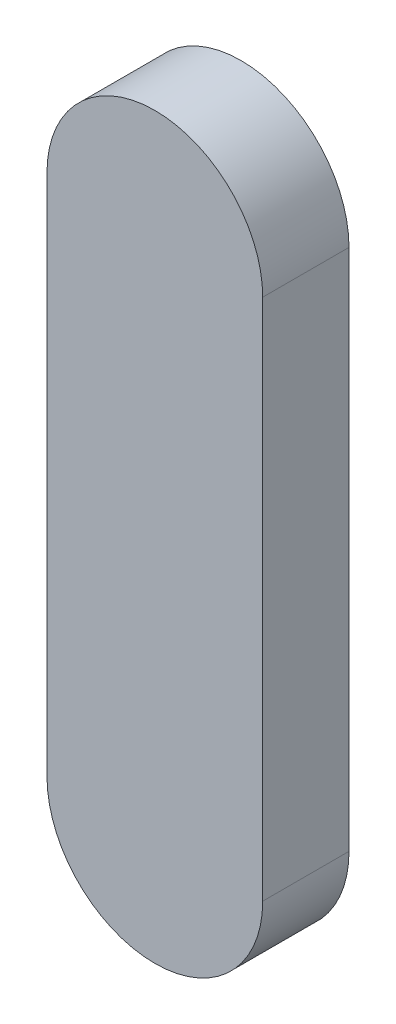
SolidWorks part; units mm, degrees
ref_plane "Front Plane" through (0, 0, 0) normal (0, 0, 1) x (1, 0, 0)
ref_plane "Top Plane" through (0, 0, 0) normal (0, 1, 0) x (1, 0, 0)
ref_plane "Right Plane" through (0, 0, 0) normal (1, 0, 0) x (0, 0, -1)
sketch "Sketch1" plane through (0, 0, 0) normal (0, 0, 1) x (1, 0, 0)
  line L2 (104.7056, -39.4482) -> (104.7056, -24.0518)
  line L3 (98.3556, -24.0518) -> (98.3556, -39.4482)
  line L4 (104.7056, -39.4482) -> (104.7056, -24.0518)
  line L5 (98.3556, -24.0518) -> (98.3556, -39.4482)
  arc A2 (98.3556, -39.4482) -> (104.7056, -39.4482) centre (101.5306, -39.4482) ccw
  arc A3 (104.7056, -24.0518) -> (98.3556, -24.0518) centre (101.5306, -24.0518) ccw
  arc A4 (98.3556, -39.4482) -> (104.7056, -39.4482) centre (101.5306, -39.4482) ccw
  arc A5 (104.7056, -24.0518) -> (98.3556, -24.0518) centre (101.5306, -24.0518) ccw
  dimension "D1" = 0
extrude "Boss-Extrude1" add sketch "Sketch1" along normal blind 2.54
